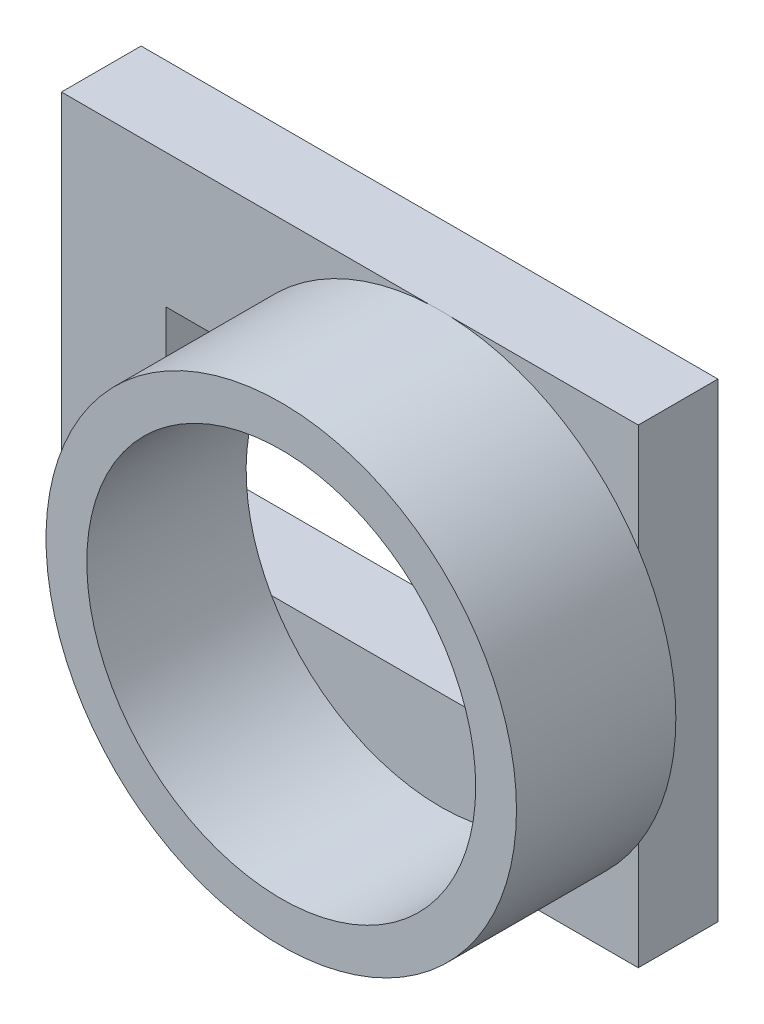
SolidWorks part; units mm, degrees
ref_plane "Front Plane" through (0, 0, 0) normal (0, 0, 1) x (1, 0, 0)
ref_plane "Top Plane" through (0, 0, 0) normal (0, 1, 0) x (1, 0, 0)
ref_plane "Right Plane" through (0, 0, 0) normal (1, 0, 0) x (0, 0, -1)
sketch "Sketch1" plane through (0, 0, 0) normal (0, 0, 1) x (1, 0, 0)
  line L1 (0, 0) -> (36.2, 0)
  line L2 (0, 0) -> (0, 29.5)
  line L3 (0, 29.5) -> (36.2, 29.5)
  line L4 (36.2, 0) -> (36.2, 29.5)
  dimension "D1" = 29.5
  dimension "D2" = 36.2
extrude "Boss-Extrude1" add sketch "Sketch1" along normal blind 5
sketch "Sketch3" plane through (0, 0, 5) normal (0, 0, 1) x (1, 0, 0)
  line L0 (18.1, 29.5) -> (18.1, 0) construction
  line L1 (1.5735, 21.1) -> (34.6265, 21.1)
  line L2 (1.5735, 21.1) -> (1.5735, 8.728)
  line L3 (1.5735, 8.728) -> (34.6265, 8.728)
  line L4 (34.6265, 21.1) -> (34.6265, 8.728)
  line L5 (36.2, 29.5) -> (0, 29.5) construction
  line L6 (0, 0) -> (36.2, 0) construction
  dimension "D1" = 33.053
  dimension "D2" = 12.372
  dimension "D3" = 16.5265
  dimension "D4" = 8.4
extrude "Cut-Extrude1" cut sketch "Sketch3" against normal through all contours L2 L1 L4 L3
sketch "Sketch4" plane through (0, 0, 5) normal (0, 0, 1) x (1, 0, 0)
  line L0 (1.5735, 8.728) -> (34.6265, 8.728) construction
  line L1 (1.5735, 21.1) -> (6.5735, 21.1)
  line L2 (1.5735, 21.1) -> (1.5735, 8.728)
  line L3 (1.5735, 8.728) -> (6.5735, 8.728)
  line L4 (6.5735, 21.1) -> (6.5735, 8.728)
  line L6 (34.6265, 21.1) -> (29.6265, 21.1)
  line L7 (34.6265, 21.1) -> (34.6265, 8.728)
  line L8 (34.6265, 8.728) -> (29.6265, 8.728)
  line L9 (29.6265, 21.1) -> (29.6265, 8.728)
  dimension "D1" = 5
  dimension "D2" = 5
extrude "Boss-Extrude2" add sketch "Sketch4" against normal blind 3.5
sketch "Sketch5" plane through (0, 0, 5) normal (0, 0, 1) x (1, 0, 0)
  line L0 (0, 14.75) -> (36.2, 14.75) construction
  line L1 (0, 29.5) -> (0, 0) construction
  line L2 (36.2, 0) -> (36.2, 29.5) construction
  circle A0 centre (23.7947, 14.75) radius 14.7637
  circle A1 centre (23.7947, 14.75) radius 12.2036
  dimension "D2" = 29.5273
  dimension "D3" = 24.4072
  dimension "D1" = 23.7947
extrude "Boss-Extrude3" add sketch "Sketch5" along normal blind 10
sketch "Sketch7" plane through (0, 0, 5) normal (0, 0, 1) x (1, 0, 0)
  line L0 (23.7947, 14.75) -> (38.5583, 14.75) construction
  line L1 (38.5583, 14.75) -> (9.031, 14.75) construction
  circle A0 centre (23.7947, 14.75) radius 14.7637 construction
  arc A1 (18.5997, 11.0436) -> (18.5997, 18.4564) centre (23.7947, 14.75) ccw
  circle A2 centre (23.7947, 14.75) radius 12.3981
  arc A3 (18.5997, 18.4564) -> (18.5997, 11.0436) centre (17.8316, 14.75) ccw
  dimension "D1" = 12.7632
  dimension "D2" = 24.7963
  dimension "D4" = 7.5703
  dimension "D3" = 5.9631
sketch "Sketch8" plane through (0, 0, 5) normal (0, 0, 1) x (1, 0, 0)
  line L1 (10.315, 8.728) -> (29.3626, 8.728)
  line L2 (10.315, 8.728) -> (10.315, 21.1)
  line L3 (10.315, 21.1) -> (29.3626, 21.1)
  line L4 (29.3626, 8.728) -> (29.3626, 21.1)
  dimension "D1" = 19.0477
  dimension "D2" = 12.372
